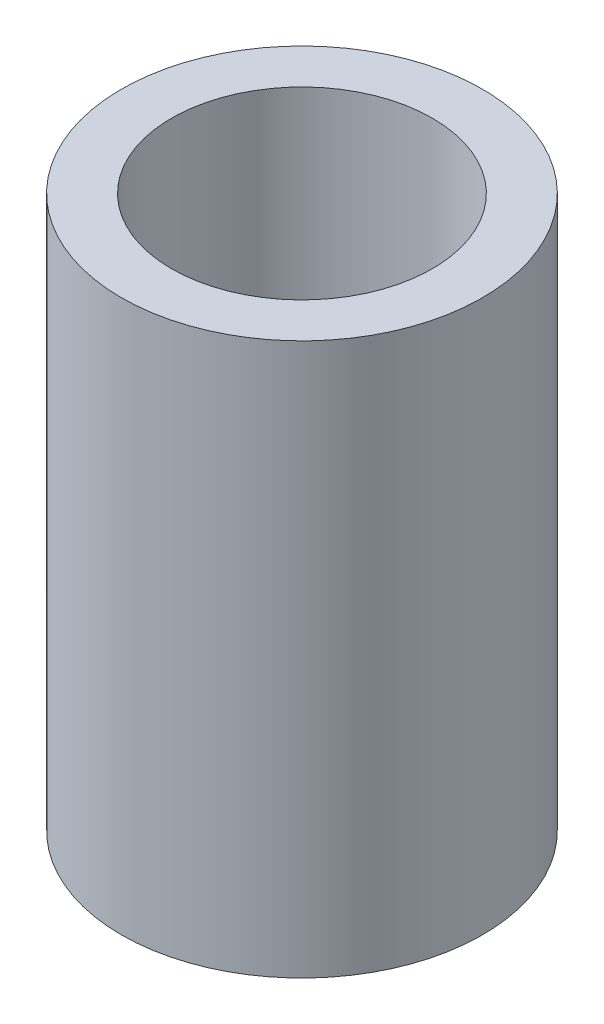
SolidWorks part; units mm, degrees
ref_plane "Front Plane" through (0, 0, 0) normal (0, 0, 1) x (1, 0, 0)
ref_plane "Top Plane" through (0, 0, 0) normal (0, 1, 0) x (1, 0, 0)
ref_plane "Right Plane" through (0, 0, 0) normal (1, 0, 0) x (0, 0, -1)
sketch "Sketch1" plane through (0, 0, 0) normal (0, 1, 0) x (1, 0, 0)
  circle A0 centre (0, 0) radius 9
  circle A1 centre (0, 0) radius 6.5
extrude "Boss-Extrude1" add sketch "Sketch1" along normal blind 12.5 and the other way blind 15
